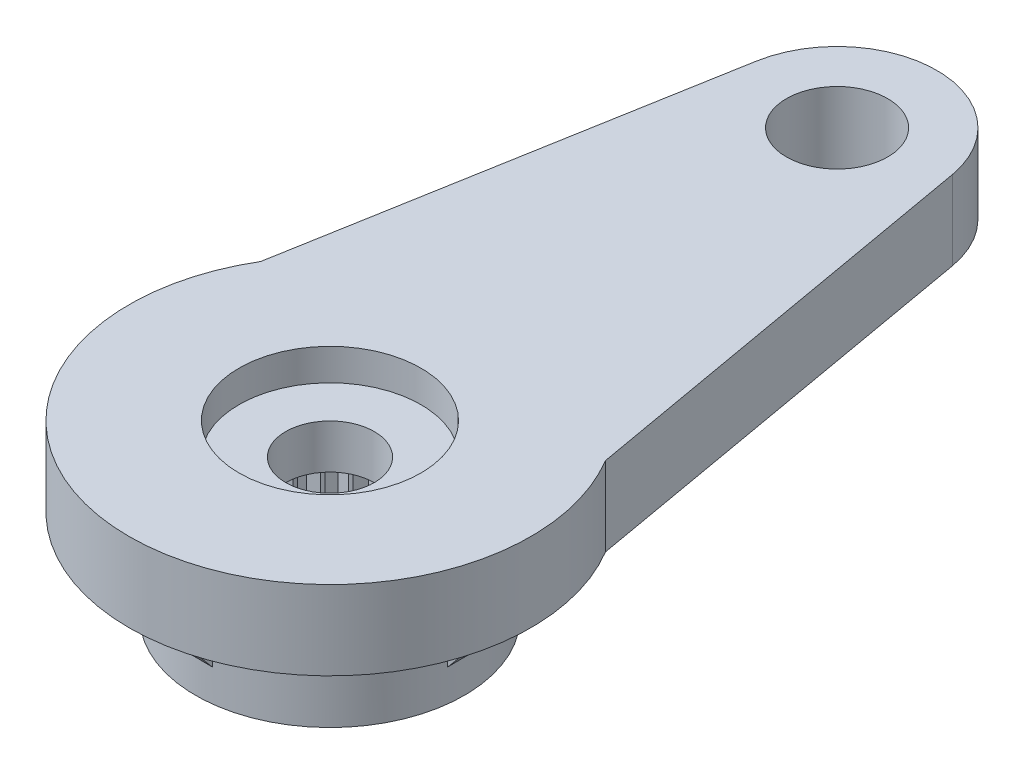
SolidWorks part; units mm, degrees
material "PC High Viscosity"
ref_plane "Front Plane" through (0, 0, 0) normal (0, 0, 1) x (1, 0, 0)
ref_plane "Top Plane" through (0, 0, 0) normal (0, 1, 0) x (1, 0, 0)
ref_plane "Right Plane" through (0, 0, 0) normal (1, 0, 0) x (0, 0, -1)
sketch "BaseS" plane through (0, 0, 0) normal (0, 1, 0) x (1, 0, 0)
  circle A0 centre (0, 0) radius 6.35
  dimension "D1" = 12.7
extrude "BASE" add sketch "BaseS" along normal blind 5.4
sketch "TopBoreS" plane through (0, 5.4, 0) normal (0, 1, 0) x (1, 0, 0)
  circle A0 centre (0, 0) radius 1.4
  dimension "D1" = 2.8
extrude "TOP BORE" cut sketch "TopBoreS" against normal through all
sketch "HornHalfS" plane through (0, 5.4, 0) normal (0, 1, 0) x (1, 0, 0)
  line L0 (0, 0) -> (0, 16.03) construction
  line L1 (-3.1021, 16.577) -> (-5.4507, 3.2577)
  line L2 (0, 19.18) -> (0, 16.03) construction
  line L3 (3.1021, 16.577) -> (5.4507, 3.2577)
  arc A0 (3.1021, 16.577) -> (-3.1021, 16.577) centre (0, 16.03) ccw
  arc A1 (5.4507, 3.2577) -> (-5.4507, 3.2577) centre (0, 0) ccw
  circle A2 centre (0, 0) radius 6.35 construction
  dimension "D1" = 6.3
  dimension "D2" = 19.18
  dimension "D3" = 10
  dimension "D4" = 10.9014
extrude "HORN HALF" add sketch "HornHalfS" against normal blind 2.5
sketch "HornAttachS" plane through (0, 5.4, 0) normal (0, 1, 0) x (1, 0, 0)
  circle A0 centre (0, 16.03) radius 1.6
  dimension "D1" = 3.2
extrude "HORN ATTACH" cut sketch "HornAttachS" against normal through all
sketch "HA LP RS" plane through (0, 0, 0) normal (0, 1, 0) x (1, 0, 0)
  line L0 (0, 0) -> (0, 16.03) construction
sketch "ToothS" plane through (0, 0, 0) normal (0, -1, 0) x (1, 0, 0)
  line L0 (0, -2.9) -> (0.2629, -2.5867)
  line L1 (0, -2.9) -> (-0.2629, -2.5867)
  line L2 (0, -2.6) -> (0, -2.9) construction
  line L3 (0, 0) -> (0, -2.6) construction
  arc A0 (-0.2629, -2.5867) -> (0.2629, -2.5867) centre (0, 0) ccw
  dimension "D1" = 5.2
  dimension "D2" = 80
  dimension "D3" = 0.3
extrude "TOOTH" cut sketch "ToothS" against normal blind 3
pattern_circular "TOOTH CP" count 26 over 360 about axis through (0, 0, 0) along (0, 1, 0) of "TOOTH"
sketch "BottomBoreS" plane through (0, 0, 0) normal (0, -1, 0) x (-1, 0, 0)
  circle A0 centre (0, 0) radius 2.6
  arc A1 (0.2629, 2.5867) -> (-0.2629, 2.5867) centre (0, 0) ccw construction
extrude "BOTTOM BORE" cut sketch "BottomBoreS" against normal up to surface (3 mm away) up to face at (-0.6451, 3, 2.6172)
sketch "HoldingShaftS" plane through (0, 0, 0) normal (0, -1, 0) x (1, 0, 0)
  circle A0 centre (0, 0) radius 6.35 construction
  circle A1 centre (0, 0) radius 6.35
  circle A2 centre (0, 0) radius 4.25
  dimension "D1" = 2.1
  dimension "D2" = 8.5
extrude "HOLDING SHAFT" cut sketch "HoldingShaftS" against normal up to surface (2.9 mm away) up to face at (0, 2.9, -14.43)
sketch "RibS" plane through (0, 0, 0) normal (0, 0, 1) x (1, 0, 0)
  line L0 (4.21, 1) -> (5.8043, 2.9)
  line L1 (5.8043, 2.9) -> (4.21, 2.9)
  line L2 (4.21, 1) -> (4.16, 1)
  line L3 (4.16, 1) -> (4.16, 2.9)
  line L4 (4.21, 1) -> (4.21, 2.9) construction
  line L5 (4.16, 2.9) -> (4.21, 2.9)
  line L6 (-4.25, 2.9) -> (4.25, 2.9) construction
  line L7 (4.21, 2.9) -> (4.25, 2.9) construction
  line L8 (4.25, 0) -> (4.25, 2.9) construction
  dimension "D1" = 1.9
  dimension "D2" = 0.05
  dimension "D3" = 40
  dimension "D4" = 0.09
extrude "RIB" add sketch "RibS" along normal mid plane 1
pattern_circular "RIB CP" count 4 over 360 about axis through (0, 0, 0) along (0, 1, 0) of "RIB"
sketch "Sketch1" plane through (0, 5.4, 0) normal (0, 1, 0) x (1, 0, 0)
  circle A0 centre (0, 0) radius 2.875
  dimension "D1" = 5.75
extrude "Cut-Extrude1" cut sketch "Sketch1" against normal blind 1
ref_point "Point1"
